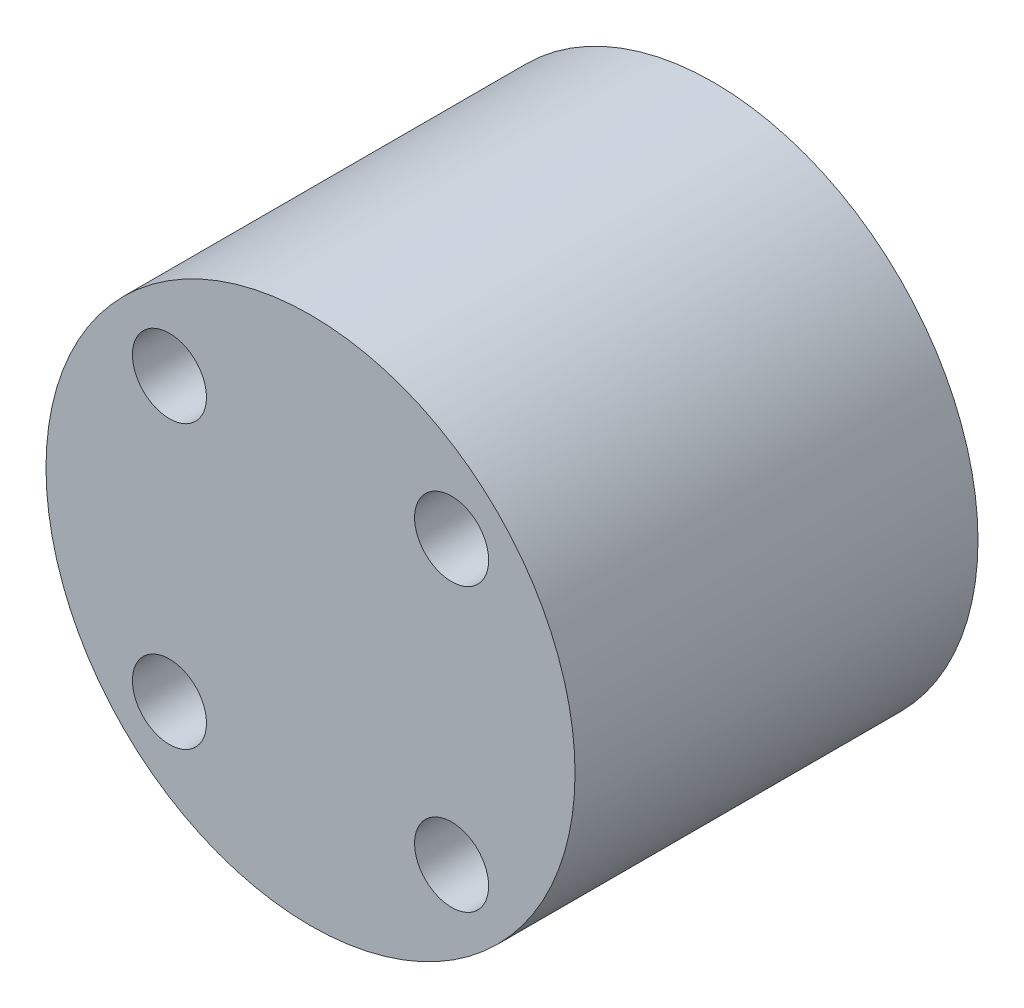
SolidWorks part; units mm, degrees
ref_plane "Front Plane" through (0, 0, 0) normal (0, 0, 1) x (1, 0, 0)
ref_plane "Top Plane" through (0, 0, 0) normal (0, 1, 0) x (1, 0, 0)
ref_plane "Right Plane" through (0, 0, 0) normal (1, 0, 0) x (0, 0, -1)
sketch "Sketch1" plane through (0, 0, 0) normal (0, 0, 1) x (1, 0, 0)
  circle A0 centre (0, 0) radius 15
  dimension "D1" = 30
extrude "Boss-Extrude1" add sketch "Sketch1" along normal mid plane 22.85
sketch "Sketch2" plane through (0, 0, 11.425) normal (0, 0, 1) x (1, 0, 0)
  circle A0 centre (-8, 8) radius 2.1
  circle A1 centre (8, 8) radius 2.1
  circle A2 centre (8, -8) radius 2.1
  circle A3 centre (-8, -8) radius 2.1
  point P2 (-8.4581, -8.4318)
  point P4 (0, 0)
  point P5 (0, 0)
  point P12 (0, 0)
  dimension "D1" = 4.2
  dimension "D2" = 8
  dimension "D3" = 8
  dimension "D4" = 4
extrude "Cut-Extrude1" cut sketch "Sketch2" against normal through all contours A0 | A1 | A2 | A3
